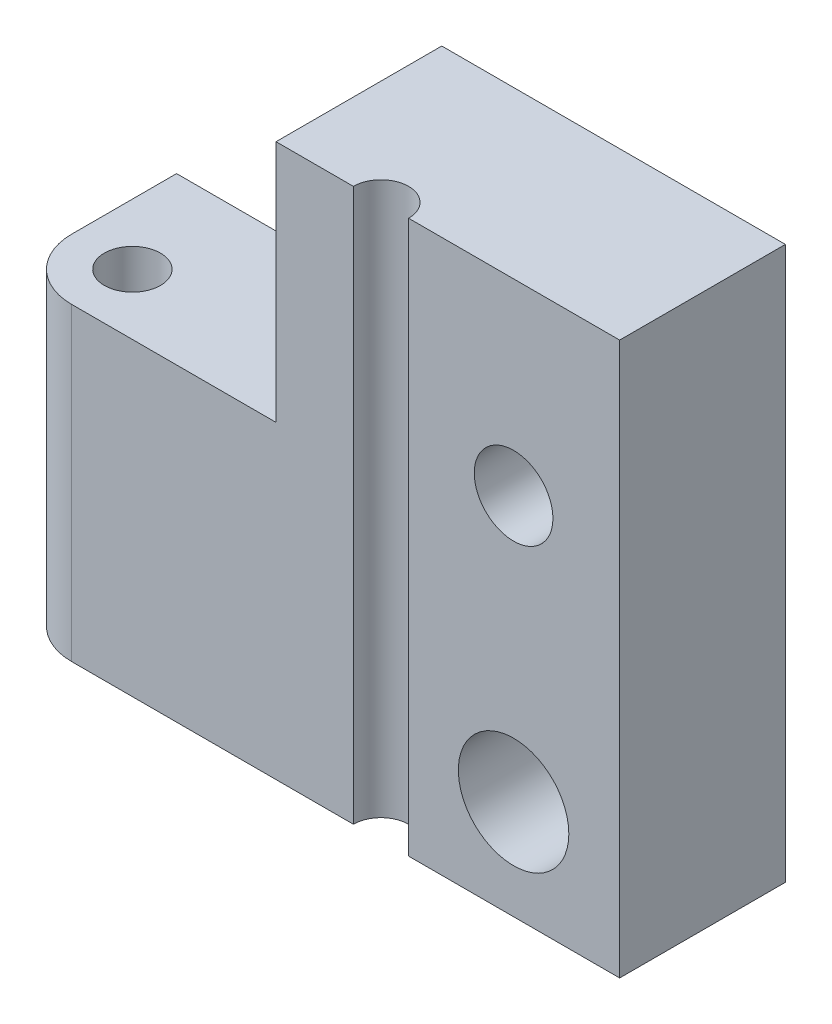
SolidWorks part; units mm, degrees
ref_plane "Front Plane" through (0, 0, 0) normal (0, 0, 1) x (1, 0, 0)
ref_plane "Top Plane" through (0, 0, 0) normal (0, 1, 0) x (1, 0, 0)
ref_plane "Right Plane" through (0, 0, 0) normal (1, 0, 0) x (0, 0, -1)
sketch "Sketch1" plane through (0, 0, 0) normal (0, 1, 0) x (1, 0, 0)
  line L2 (0, 1.7462) -> (0, 3.175)
  line L7 (0, 3.175) -> (17.4943, 3.175)
  line L8 (17.4943, 0) -> (17.4943, 3.175)
  line L16 (0, 1.7462) -> (0, 0) construction
  line L17 (0, 0) -> (1.7463, 0) construction
  line L18 (-1.3895, -0.7937) -> (22.6268, -0.7938) construction
  line L19 (1.7463, 0) -> (9.8425, 0)
  line L21 (11.43, 0) -> (17.4943, 0)
  circle A0 centre (1.7463, 1.7462) radius 0.7938 construction
  arc A1 (0, 1.7462) -> (1.7463, 0) centre (1.7463, 1.7462) ccw
  circle A2 centre (10.6362, 0) radius 0.7937 construction
  arc A3 (9.8425, 0) -> (11.43, 0) centre (10.6362, 0) cw
  dimension "D7" = 1.5875
  dimension "D4" = 1.5875
  dimension "D1" = 2.54
  dimension "D3" = 3.175
  dimension "D2" = 15.748
  dimension "D9" = 8.89
extrude "Boss-Extrude1" add sketch "Sketch1" along normal blind 15.875
hole_wizard "#52 (0.0635) Diameter Hole1" positions "3DSketch1" profile "Sketch2" hole size "#52" standard "ANSI Inch" end condition through all
sketch3d "3DSketch1"
  line L0 (0, 15.875, -3.175) -> (0, 15.875, -1.7462) construction
  line L2 (1.7463, 15.875, 0) -> (9.8425, 15.875, 0) construction
  point P0 (1.7463, 15.875, -1.7463)
  dimension "D1" = 1.7463
  dimension "D2" = 1.7463
sketch "Sketch2" plane through (1.7463, 15.875, -1.7463) normal (1, 0, 0) x (0, 0, 1)
  line L0 (0, 0) -> (0, 15.875)
  line L1 (0, 15.875) -> (0.8064, 15.875)
  line L2 (0.8064, 15.875) -> (0.8064, 0)
  line L5 (0.8064, 0) -> (0, 0)
  line L11 (0, -6.35) -> (0, 107.95) construction
  dimension "Thru Hole Dia." = 1.6129
  dimension "Thru Hole Depth" = 15.875
sketch "Sketch3" plane through (0, 0, -3.175) normal (0, 0, -1) x (-1, 0, 0)
  line L0 (-17.4943, 0) -> (0, 0) construction
  line L1 (0, 15.875) -> (0, 0) construction
  line L5 (0, 15.875) -> (-7.62, 15.875)
  line L6 (0, 15.875) -> (0, 8.89)
  line L7 (0, 8.89) -> (-7.62, 8.89)
  line L8 (-7.62, 15.875) -> (-7.62, 8.89)
  circle A0 centre (-14.4462, 5.08) radius 1.5875 construction
  circle A1 centre (-14.4463, 12.7) radius 1.5875 construction
  dimension "D4" = 3.175
  dimension "D1" = 5.08
  dimension "D2" = 7.62
  dimension "D3" = 8.89
  dimension "D5" = 14.4462
  dimension "D6" = 7.62
extrude "Cut-Extrude1" cut sketch "Sketch3" against normal through all
sketch "Sketch5" plane through (0, 0, 0) normal (0, 0, 1) x (1, 0, 0)
  line L0 (1.7462, 8.89) -> (1.7463, 0) construction
  line L2 (17.4943, 0) -> (0, 0) construction
  circle A0 centre (14.4462, 2.8575) radius 1.5875
  dimension "D3" = 3.175
  dimension "D1" = 12.7
  dimension "D2" = 2.8575
extrude "Cut-Extrude2" cut sketch "Sketch5" against normal blind 3.302
sketch "Sketch7" plane through (0, 0, -3.175) normal (0, 0, -1) x (-1, 0, 0)
  line L8 (-17.4943, 0) -> (0, 0)
  line L11 (0, 0) -> (0, 8.89)
  line L12 (0, 8.89) -> (-7.62, 8.89)
  line L13 (-7.62, 8.89) -> (-7.62, 15.875)
  line L14 (-7.62, 15.875) -> (-17.4943, 15.875)
  line L15 (-17.4943, 15.875) -> (-17.4943, 0)
  line L16 (-17.4943, 0) -> (0, 0)
  line L19 (0, 0) -> (0, 8.89)
  line L20 (0, 8.89) -> (-7.62, 8.89)
  line L21 (-7.62, 8.89) -> (-7.62, 15.875)
  line L22 (-7.62, 15.875) -> (-17.4943, 15.875)
  line L23 (-17.4943, 15.875) -> (-17.4943, 0)
  dimension "D1" = 0
extrude "Boss-Extrude2" add sketch "Sketch7" along normal blind 1.5875
hole_wizard "#4-40 Tapped Hole1" positions "3DSketch2" profile "Sketch6" tap size "#4-40" standard "ANSI Inch" end condition through all
sketch3d "3DSketch2"
  circle A0 centre (14.4462, 2.8575, 0) radius 1.5875 construction
  circle A1 centre (14.4462, 2.8575, 0) radius 1.5875 construction
  point P0 (14.4462, 10.4775, 0)
  point P7 (14.4462, 2.8575, 1.5875)
  point P9 (14.4462, 2.8575, 1.5875)
  dimension "D1" = 7.62
sketch "Sketch6" plane through (14.4462, 10.4775, 0) normal (1, 0, 0) x (0, -1, 0)
  line L0 (0, 0) -> (0, 4.7625)
  line L1 (0, 4.7625) -> (1.1303, 4.7625)
  line L2 (1.1303, 4.7625) -> (1.1303, 0)
  line L5 (1.1303, 0) -> (0, 0)
  line L11 (0, -6.35) -> (0, 107.95) construction
  dimension "Thru Tap Drill Dia." = 2.2606
  dimension "Thru Tap Drill Depth" = 4.7625
cosmetic thread "Hole Thread1" parameters "D2"=4.1656
hole_wizard "1/16 (0.0625) Diameter Hole1" positions "3DSketch3" profile "Sketch8" hole size "1/16" standard "ANSI Inch" end condition through all
sketch3d "3DSketch3"
  line L0 (14.4462, 2.8575, -3.175) -> (14.4462, 2.8575, 0) construction
  point P0 (14.4462, 2.8575, -3.175)
sketch "Sketch8" plane through (14.4462, 2.8575, -3.175) normal (1, 0, 0) x (0, -1, 0)
  line L0 (0, 0) -> (0, 1.5875)
  line L1 (0, 1.5875) -> (0.7937, 1.5875)
  line L2 (0.7937, 1.5875) -> (0.7937, 0)
  line L5 (0.7937, 0) -> (0, 0)
  line L11 (0, -6.35) -> (0, 107.95) construction
  dimension "Thru Hole Dia." = 1.5875
  dimension "Thru Hole Depth" = 1.5875
equation "\"D1@3DSketch1\"=\"D2@3DSketch1\""
